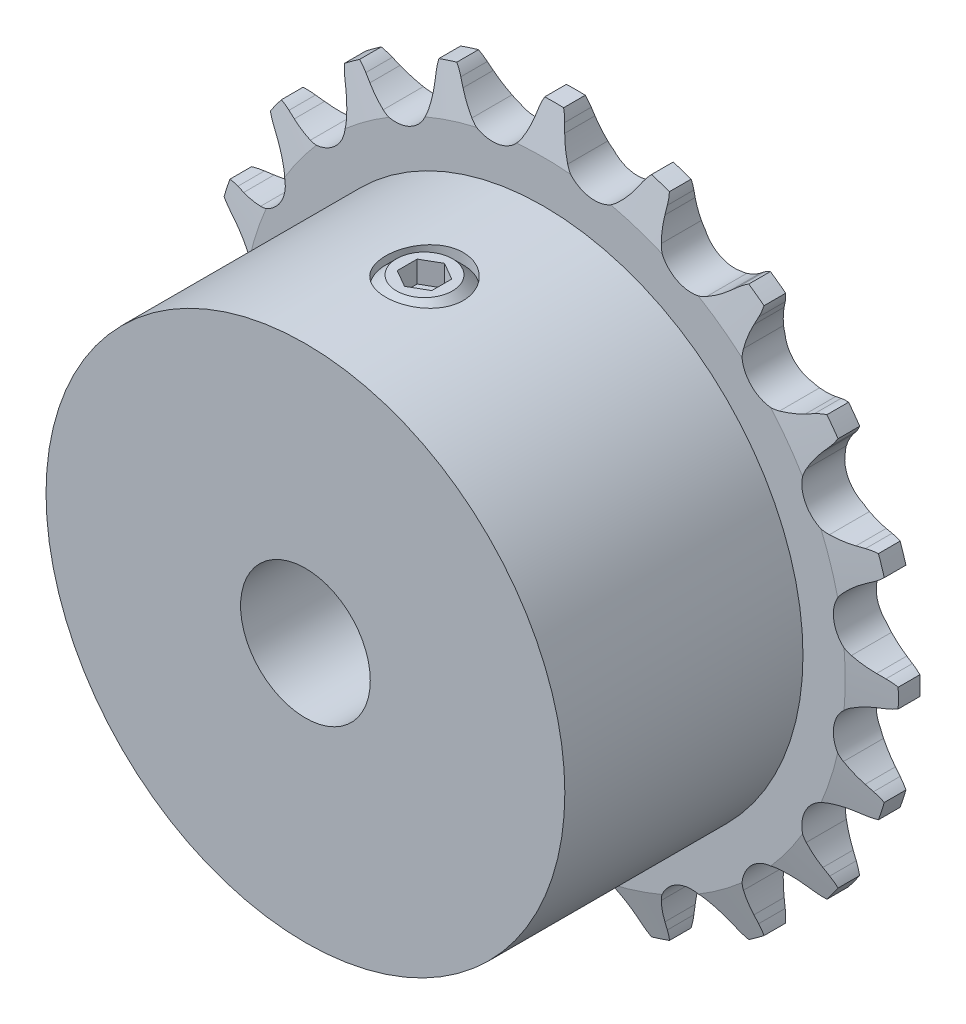
SolidWorks part; units mm, degrees
material "6061 Alloy"
ref_plane "Front Plane" through (0, 0, 0) normal (0, 0, 1) x (1, 0, 0)
ref_plane "Top Plane" through (0, 0, 0) normal (0, 1, 0) x (1, 0, 0)
ref_plane "Right Plane" through (0, 0, 0) normal (1, 0, 0) x (0, 0, -1)
sketch "Sketch0" plane through (0, 0, 0) normal (0, 0, 1) x (1, 0, 0)
  line L0 (1.8733, -11.8272) -> (0, 0) construction
  line L1 (0, 0) -> (5.4364, -10.6695) construction
  line L2 (0, 0) -> (-1.8732, -11.8272) construction
  line L3 (1.8733, -11.8272) -> (5.4364, -10.6695) construction
  line L4 (1.8733, -11.8272) -> (-1.8732, -11.8272) construction
  line L5 (3.3386, -11.8169) -> (3.189, -11.5756)
  line L6 (1.8733, -11.8272) -> (0, -12.1239) construction
  line L7 (0.4765, -12.2702) -> (0.5442, -11.9945)
  line L8 (0, -11.8272) -> (0, -12.9512) construction
  line L9 (2.6827, -10.9593) -> (0.626, -13.1647) construction
  line L10 (0, 0) -> (0, -11.8272) construction
  line L11 (3.189, -11.5756) -> (0.626, -13.1647) construction
  line L12 (0, -12.9512) -> (0, -13.1264) construction
  line L13 (4.917, -10.8383) -> (3.3386, -11.8169) construction
  circle A0 centre (0, 0) radius 12.9512 construction
  circle A1 centre (0, 0) radius 11.9747 construction
  arc A2 (-1.5343, -13.6729) -> (5.6843, -12.5296) centre (0, 0) ccw
  circle A3 centre (0, 0) radius 13.1264 construction
  circle A4 centre (1.8733, -11.8272) radius 1.143 construction
  arc A7 (2.6827, -10.9593) -> (0.8352, -11.2519) centre (1.8733, -11.8272) ccw
  circle A8 centre (1.8733, -11.8272) radius 1.1868 construction
  arc A9 (3.3386, -11.8169) -> (5.6843, -12.5296) centre (4.917, -10.8383) ccw
  arc A10 (3.189, -11.5756) -> (2.6827, -10.9593) centre (0.626, -13.1647) ccw
  arc A11 (0.4765, -12.2702) -> (-1.5343, -13.6729) centre (-1.3271, -11.8272) cw
  arc A12 (0.5442, -11.9945) -> (0.8352, -11.2519) centre (3.4728, -12.7139) cw
  dimension "D1" = 1.1868
  dimension "Dr" = 2.286
  dimension "Ds" = 2.3736
  dimension "R" = 1.1868
  dimension "Pitch" = 3.7465
  dimension "A" = 38
  dimension "360/N" = 18
  dimension "B" = 15.2
  dimension "ab" = 3.2004
  dimension "J" = 1.1239
  dimension "ac" = 1.8288
sketch "Sketch1" plane through (0, 0, 0) normal (1, 0, 0) x (0, 0, -1)
  line L0 (0.7874, 0) -> (-0.7874, 0)
  line L1 (-0.7874, 0) -> (-0.7874, 11.0779)
  line L2 (-0.7874, 11.0779) -> (-0.3191, 12.9512)
  line L3 (-0.3191, 12.9512) -> (0.3191, 12.9512)
  line L4 (0.3191, 12.9512) -> (0.7874, 11.0779)
  line L5 (0.7874, 11.0779) -> (0.7874, 0)
  line L7 (0, 12.9512) -> (0, 0) construction
  line L8 (-0.7874, 11.0779) -> (0.7874, 11.0779) construction
  line L9 (0, 12.9512) -> (0, -12.9512) construction
  line L10 (-0.7874, 11.0779) -> (-0.7874, 12.9512) construction
  line L11 (-0.7874, 12.9512) -> (-0.3191, 12.9512) construction
  line L12 (0.3191, 12.9512) -> (0.7874, 12.9512) construction
  line L13 (0.7874, 12.9512) -> (0.7874, 11.0779) construction
  line L22 (0.7874, 0) -> (-9.5313, 0) construction
  line L24 (-0.7874, 0) -> (-0.7874, 9.573) construction
  dimension "t" = 1.5748
  dimension "g" = 0.4683
  dimension "h" = 1.8732
  dimension "MHD" = 19.146
  dimension "Width" = 10.3187
revolve "Revolve1" add sketch "Sketch1" angle 360 mid plane about L0
extrude "Cut-Extrude1" cut sketch "Sketch0" against normal through all and the other way through all
pattern_circular "CirPattern1" count 20 over 360 about axis through (0, 0, 0) along (0, 0, 1) of "Cut-Extrude1"
sketch "Sketch2" plane through (0, 0, 0) normal (0, 0, 1) x (1, 0, 0)
  line L0 (0, 0) -> (0, 9.525) construction
  circle A0 centre (0, 0) radius 2.3813 construction
  circle A1 centre (0, 0) radius 9.525
  circle A2 centre (0, 0) radius 12.6365 construction
  dimension "Bore" = 4.7625
  dimension "Hub Dia." = 19.05
  dimension "OD" = 25.273
extrude "Boss-Extrude1" add sketch "Sketch2" along normal up to vertex (9.5313 mm away) from surface at 0.7874 starting at face at (0, 0, 0.7874)
sketch "Sketch3" plane through (0, 0, 0) normal (0, 0, 1) x (1, 0, 0)
  circle A0 centre (0, 0) radius 2.3813 construction
  circle A1 centre (0, 0) radius 2.3813
  circle A2 centre (0, 0) radius 12.6365 construction
  circle A3 centre (0, 0) radius 12.6365
extrude "Cut-Extrude2" cut sketch "Sketch3" along normal through all and the other way through all flip side to cut
sketch "Sketch4" plane through (0, 0, 0) normal (1, 0, 0) x (0, 0, -1)
  line L1 (-0.7874, 12.9512) -> (-3.1686, 12.9512)
  line L2 (-0.7874, 12.9512) -> (-0.7874, 9.573)
  line L3 (-0.7874, 9.573) -> (-3.1686, 9.573)
  line L4 (-3.1686, 12.9512) -> (-3.1686, 9.573)
  dimension "D1" = 2.3813
revolve "Cut-Revolve1" [suppressed] cut sketch "Sketch4" angle 360 mid plane about L22
ref_plane "Plane1" through (0, 9.525, 0) normal (0, 1, 0) x (-1, 0, 0)
sketch "Sketch5" plane through (0, 9.525, 0) normal (0, 1, 0) x (-1, 0, 0)
  line L0 (0, 0) -> (0, 0.7874) construction
  line L1 (0, 9.5313) -> (0, 0.7874) construction
  line L2 (9.525, 0.7874) -> (-9.525, 0.7874) construction
  line L3 (2.3813, 9.5313) -> (-2.3813, 9.5313) construction
  circle A0 centre (0, 5.1594) radius 1.4224
  circle A1 centre (0, 5.1594) radius 0.7874 construction
  circle A2 centre (0, 5.1594) radius 1.0255 construction
  dimension "D1" = 0.3969
  dimension "Screw OD" = 2.8448
  dimension "Pitch" = 0.635
extrude "Cut-Extrude3" cut sketch "Sketch5" against normal up to surface (9.525 mm away) up to plane "Top Plane"
sketch "Sketch6" plane through (0, 0, 0) normal (1, 0, 0) x (0, 0, -1)
  line L0 (-5.1594, 9.525) -> (-5.1594, 2.3813)
  line L1 (-5.1594, 2.3813) -> (-6.1849, 2.3812)
  line L2 (-6.1849, 2.3812) -> (-6.5818, 2.7781)
  line L3 (-6.5818, 2.7781) -> (-6.5818, 9.1281)
  line L4 (-6.5818, 9.1281) -> (-6.1849, 9.525)
  line L5 (-6.1849, 9.525) -> (-5.1594, 9.525)
  line L6 (-5.1594, 2.3813) -> (-5.1594, 0) construction
  line L7 (-5.1594, 0) -> (0, 0) construction
  line L10 (-6.5818, 2.3813) -> (-9.5313, 2.3813) construction
  line L11 (-6.5818, 9.1281) -> (-6.5818, 9.525) construction
  line L12 (-6.5818, 9.525) -> (-6.1849, 9.525) construction
revolve "Revolve2" add sketch "Sketch6" angle 360 mid plane about L6
sketch "Sketch7" plane through (0, 9.525, 0) normal (0, 1, 0) x (1, 0, 0)
  line L1 (0, -4.4261) -> (-0.635, -4.7928)
  line L2 (-0.635, -4.7928) -> (-0.635, -5.526)
  line L3 (-0.635, -5.526) -> (0, -5.8926)
  line L4 (0, -5.8926) -> (0.635, -5.526)
  line L5 (0.635, -5.526) -> (0.635, -4.7928)
  line L6 (0.635, -4.7928) -> (0, -4.4261)
  circle A0 centre (0, -5.1594) radius 0.635 construction
  dimension "Hex" = 1.27
extrude "Cut-Extrude4" cut sketch "Sketch7" against normal blind 0.7937
equation "\"360/N@Sketch0\" = 360/\"Teeth@CirPattern1\""
equation "\"Ds@Sketch0\" = 1.005 * \"Dr@Sketch0\" + 0.003"
equation "\"R@Sketch0\" = 1/2 * \"Ds@Sketch0\""
equation "\"A@Sketch0\" = 35 +  ( 60 / \"Teeth@CirPattern1\" ) "
equation "\"B@Sketch0\" = 18 -  ( 56 / \"Teeth@CirPattern1\" )"
equation "\"ac@Sketch0\" = 0.8 * \"Dr@Sketch0\""
equation "\"ab@Sketch0\" = 1.4 * \"Dr@Sketch0\""
equation "\"J@Sketch0\" = 0.3 * \"Pitch@Sketch0\""
equation "\"h@Sketch1\" = \"Pitch@Sketch0\" / 2"
equation "\"g@Sketch1\" = \"h@Sketch1\" / 4"
equation "\"MHD@Sketch1\" = \"Pitch@Sketch0\" * ( cotan ( 180 / \"Teeth@CirPattern1\" ) - 1 ) - 0.030"
equation "\"D1@Cut-Extrude4\" = \"Hex@Sketch7\" * 5 / 8"
equation "\"D1@Sketch5\" = \"Pitch@Sketch5\" * 5 / 8"
